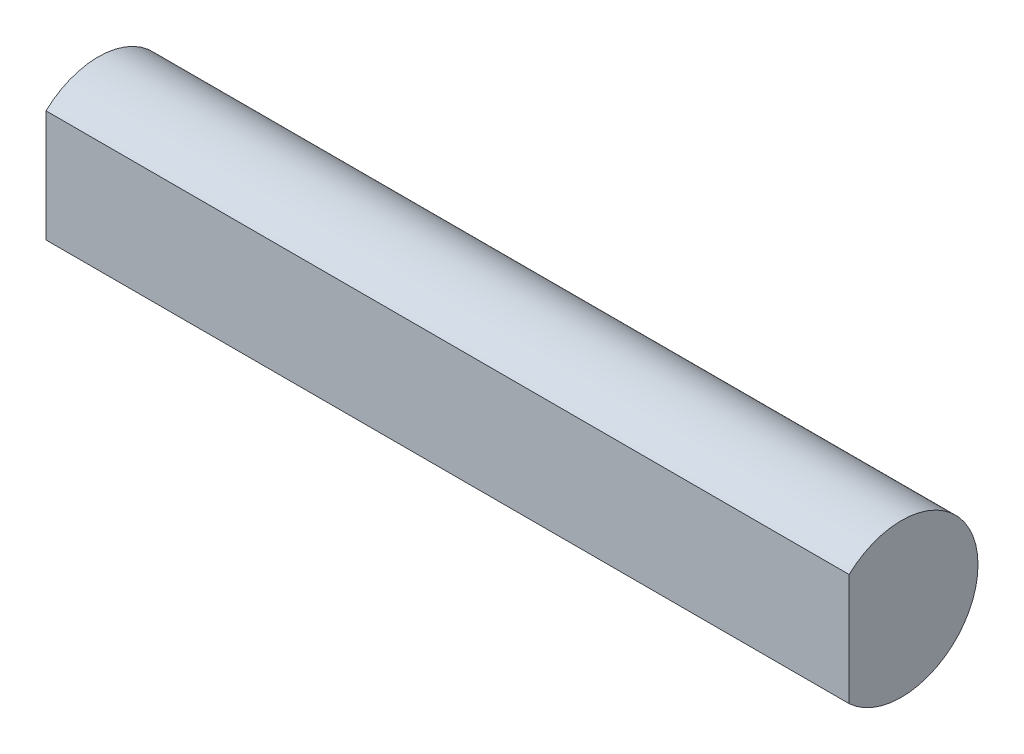
SolidWorks part; units mm, degrees
ref_plane "Alzado" through (0, 0, 0) normal (0, 0, 1) x (1, 0, 0)
ref_plane "Planta" through (0, 0, 0) normal (0, 1, 0) x (1, 0, 0)
ref_plane "Vista lateral" through (0, 0, 0) normal (1, 0, 0) x (0, 0, -1)
sketch "Croquis1" plane through (0, 0, 0) normal (1, 0, 0) x (0, 0, -1)
  line L0 (0, 0) -> (4.1, 0)
  line L1 (4.1, 0) -> (-2.8, 0)
  line L2 (-2.8, 0) -> (-2.8, -2.995)
  line L3 (-2.8, -2.995) -> (-2.8, 2.995)
  circle A0 centre (0, 0) radius 4.1
extrude "Saliente-Extruir1" add sketch "Croquis1" along normal blind 43 contours L0 A0 L3 L1 | L2 A0 L0 L1
